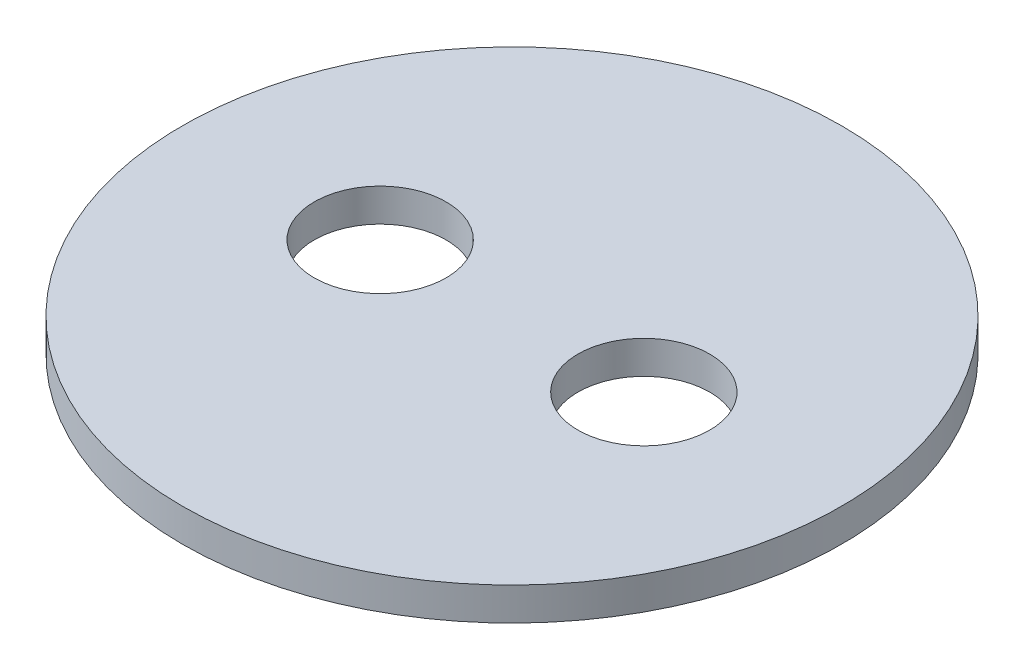
SolidWorks part; units mm, degrees
ref_plane "Front Plane" through (0, 0, 0) normal (0, 0, 1) x (1, 0, 0)
ref_plane "Top Plane" through (0, 0, 0) normal (0, 1, 0) x (1, 0, 0)
ref_plane "Right Plane" through (0, 0, 0) normal (1, 0, 0) x (0, 0, -1)
sketch "Sketch1" plane through (0, 0, 0) normal (0, 1, 0) x (1, 0, 0)
  line L0 (0, 10) -> (0, -10) construction
  line L1 (-10, 0) -> (10, 0) construction
  circle A0 centre (0, 0) radius 10
  circle A1 centre (-4, 0) radius 2
  circle A2 centre (4, 0) radius 2
  dimension "D1" = 4
  dimension "D2" = 20
  dimension "D3" = 4
extrude "Boss-Extrude1" add sketch "Sketch1" along normal blind 1
